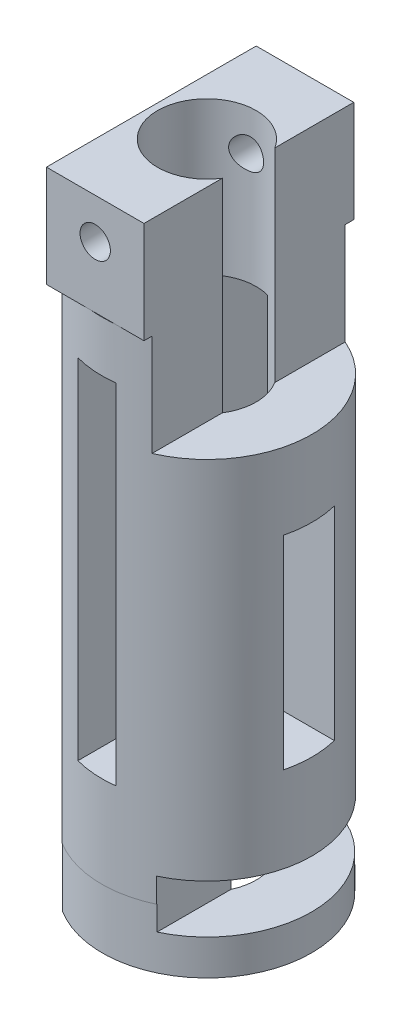
SolidWorks part; units mm, degrees
ref_plane "前基準面" through (0, 0, 0) normal (0, 0, 1) x (1, 0, 0)
ref_plane "上基準面" through (0, 0, 0) normal (0, 1, 0) x (1, 0, 0)
ref_plane "右基準面" through (0, 0, 0) normal (1, 0, 0) x (0, 0, -1)
sketch "草圖1" plane through (0, 0, 0) normal (0, 1, 0) x (1, 0, 0)
  circle A0 centre (0, 0) radius 9.7
  dimension "D1" = 19.4
extrude "伸長-薄件1" add sketch "草圖1" along normal blind 116.68 thin
ref_plane "平面1" through (-21, 0, 0) normal (1, 0, 0) x (0, 0, -1)
sketch "草圖11" plane through (0, 116.68, 0) normal (0, 1, 0) x (1, 0, 0)
  line L0 (-993.1634, -44.2358) -> (49006.8366, -44.2358) construction
  line L2 (35.2085, 30.7642) -> (8.2085, 30.7642)
  line L3 (35.2085, 30.7642) -> (35.2085, -119.2358)
  line L4 (35.2085, -119.2358) -> (8.2085, -119.2358)
  line L5 (8.2085, 30.7642) -> (8.2085, -119.2358)
  line L6 (35.2085, 30.7642) -> (8.2085, -119.2358) construction
  line L7 (35.2085, -119.2358) -> (8.2085, 30.7642) construction
  circle A0 centre (0, 0) radius 20.7 construction
  point P1 (21.7085, -44.2358)
  dimension "D1" = 150
  dimension "D2" = 27
  dimension "D3" = 30.7642
extrude "除料-伸長3" cut sketch "草圖11" against normal blind 40
ref_plane "平面2" through (0, 0, 21) normal (0, 0, 1) x (1, 0, 0)
sketch "草圖13" plane through (0, 0, 21) normal (0, 0, 1) x (1, 0, 0)
  line L0 (-21, -22.649) -> (-21, 22.649) construction
  line L1 (-21, 122.7847) -> (-11, 122.7847)
  line L2 (-21, 122.7847) -> (-21, -5.5603)
  line L3 (-21, -5.5603) -> (-11, -5.5603)
  line L4 (-11, 122.7847) -> (-11, -5.5603)
  dimension "D1" = 10
extrude "除料-伸長7" cut sketch "草圖13" against normal through all
sketch "草圖15" plane through (0, 0, 21) normal (0, 0, 1) x (1, 0, 0)
  line L0 (-1.3957, -883.32) -> (-1.3957, 49116.68) construction
  line L1 (8.2085, 116.68) -> (-11, 116.68) construction
  line L2 (-11, 0) -> (20.7, 0) construction
  line L3 (2.6043, 86.68) -> (-5.3957, 86.68)
  line L4 (2.6043, 86.68) -> (2.6043, 18)
  line L5 (2.6043, 18) -> (-5.3957, 18)
  line L6 (-5.3957, 86.68) -> (-5.3957, 18)
  line L7 (2.6043, 86.68) -> (-5.3957, 18) construction
  line L8 (2.6043, 18) -> (-5.3957, 86.68) construction
  point P1 (-1.3957, 52.34)
  point P5 (-1.3957, 116.68)
  dimension "D1" = 30
  dimension "D2" = 18
  dimension "D3" = 8
extrude "除料-伸長9" cut sketch "草圖15" against normal blind 48
sketch "草圖16" plane through (8.2085, 0, 0) normal (1, 0, 0) x (0, 0, -1)
  line L0 (20.7, 86.68) -> (20.7, 116.68) construction
  line L1 (5.1682, 116.68) -> (20.7, 116.68)
  line L2 (5.1682, 116.68) -> (5.1682, 96.68)
  line L3 (5.1682, 96.68) -> (20.7, 96.68)
  line L4 (20.7, 116.68) -> (20.7, 96.68)
  line L5 (-5.1682, 76.68) -> (-5.1682, 116.68) construction
  line L6 (-5.1682, 96.68) -> (-20.59, 96.68)
  line L7 (-5.1682, 96.68) -> (-5.1682, 116.68)
  line L8 (-5.1682, 116.68) -> (-20.59, 116.68)
  line L9 (-20.59, 96.68) -> (-20.59, 116.68)
  line L10 (-17.5354, 116.68) -> (-20.7, 116.68) construction
  dimension "D1" = 20
extrude "填料-伸長4" add sketch "草圖16" against normal blind 19.2
sketch "草圖17" plane through (0, 116.68, 0) normal (0, 1, 0) x (1, 0, 0)
  line L0 (-1009.59, 0) -> (48990.41, 0) construction
  line L1 (8.2085, 20.7) -> (8.2085, 5.1682) construction
  line L2 (8.2085, 6.97) -> (-11, 6.97)
  line L3 (8.2085, 6.97) -> (8.2085, -7.06)
  line L4 (8.2085, -7.06) -> (-11, -7.06)
  line L5 (-11, 6.97) -> (-11, -7.06)
  line L6 (-11, -17.5354) -> (-11, 17.5354) construction
  line L7 (-10.9915, -20.59) -> (-2.1312, -20.59) construction
  arc A0 (-8.2085, 5.1682) -> (-8.2085, -5.1682) centre (0, 0) ccw construction
  point P6 (-9.7, 0)
  dimension "D1" = 14.03
  dimension "D2" = 13.53
sketch "草圖21" plane through (0, 0, -20.7) normal (0, 0, -1) x (-1, 0, 0)
  line L0 (1.3915, 96.68) -> (1.3915, 105.73) construction
  line L1 (0, 96.68) -> (10.9915, 96.68) construction
  line L2 (1.3915, 105.73) -> (1.3915, 108.73) construction
  circle A0 centre (1.3915, 108.73) radius 2.985
  dimension "D3" = 5.97
  dimension "D1" = 9.05
  dimension "D2" = 3
extrude "除料-伸長12" cut sketch "草圖21" against normal blind 55.2
sketch "草圖23" plane through (0, 0, -20.7) normal (0, 0, -1) x (-1, 0, 0)
  line L0 (1.3915, 105.745) -> (1.3915, -11.785) construction
  circle A0 centre (1.3915, 108.73) radius 2.985 construction
  dimension "D1" = 117.53
sketch "草圖24" plane through (0, 0, 0) normal (0, -1, 0) x (1, 0, 0)
  circle A0 centre (0, 0) radius 9.59
extrude "伸長-薄件2" add sketch "草圖24" along normal blind 55.2 thin
sketch "草圖25" plane through (0, 0, 21) normal (0, 0, 1) x (1, 0, 0)
  line L0 (-1.3915, -11.785) -> (22.6124, -11.785)
  line L1 (22.6124, -11.785) -> (22.6124, -63.8733)
  line L2 (-22.7495, -63.8733) -> (22.6124, -63.8733)
  line L3 (-22.7495, -63.8733) -> (-22.7495, -11.785)
  line L4 (-22.7495, -11.785) -> (-1.3915, -11.785)
extrude "除料-伸長13" cut sketch "草圖25" against normal blind 55.2
sketch "草圖26" plane through (0, 0, 0) normal (0, 1, 0) x (1, 0, 0)
  line L0 (-21, -22.649) -> (-21, 22.649) construction
  line L1 (-10.9915, 20.7) -> (-21, 20.7)
  line L2 (-10.9915, 20.7) -> (-10.9915, -21)
  line L3 (-10.9915, -21) -> (-21, -21)
  line L4 (-21, 20.7) -> (-21, -21)
  line L5 (-25.6693, -21) -> (25.6693, -21) construction
extrude "除料-伸長15" cut sketch "草圖26" against normal blind 55.2
ref_plane "平面3" through (21, 0, 0) normal (1, 0, 0) x (0, 0, -1)
sketch "草圖27" plane through (21, 0, 0) normal (1, 0, 0) x (0, 0, -1)
  line L0 (0, -923.32) -> (0, 49076.68) construction
  line L1 (5.1682, 76.68) -> (-5.1682, 76.68) construction
  line L2 (19.0029, 76.68) -> (-19.0029, 76.68) construction
  line L3 (-5, 61.68) -> (5, 61.68)
  line L4 (-5, 61.68) -> (-5, 21.68)
  line L5 (-5, 21.68) -> (5, 21.68)
  line L6 (5, 61.68) -> (5, 21.68)
  line L7 (-5, 61.68) -> (5, 21.68) construction
  line L8 (-5, 21.68) -> (5, 61.68) construction
  point P1 (0, 41.68)
  point P5 (0, 76.68)
  dimension "D1" = 15
  dimension "D2" = 40
  dimension "D3" = 10
extrude "除料-伸長16" cut sketch "草圖27" against normal blind 55.2
sketch "草圖28" plane through (21, 0, 0) normal (1, 0, 0) x (0, 0, -1)
  line L1 (-22.4403, 4.804) -> (22.4403, 4.804)
  line L2 (-22.4403, 4.804) -> (-22.4403, -4.804)
  line L3 (-22.4403, -4.804) -> (22.4403, -4.804)
  line L4 (22.4403, 4.804) -> (22.4403, -4.804)
  line L5 (-22.4403, 4.804) -> (22.4403, -4.804) construction
  line L6 (-22.4403, -4.804) -> (22.4403, 4.804) construction
  point P0 (0, 0)
extrude "除料-伸長17" cut sketch "草圖28" against normal blind 12.2
ref_plane "平面4" through (0, 0, 50) normal (0, 0, 1) x (1, 0, 0)
sketch "草圖63" plane through (0, -11.785, 0) normal (0, -1, 0) x (1, 0, 0)
  circle A0 centre (0, 0) radius 9.59
extrude "除料-伸長36" cut sketch "草圖63" against normal blind 130
sketch "草圖64" plane through (0, -11.785, 0) normal (0, -1, 0) x (1, 0, 0)
  circle A0 centre (0, 0) radius 9.7
  dimension "D1" = 19.4
extrude "除料-伸長37" cut sketch "草圖64" against normal through all
sketch "草圖66" plane through (0, 116.68, 0) normal (0, 1, 0) x (1, 0, 0)
  line L1 (2.1312, -20.59) -> (-2.1879, -20.59)
  line L2 (2.1312, -20.59) -> (2.1312, -21.3905)
  line L3 (2.1312, -21.3905) -> (-2.1879, -21.3905)
  line L4 (-2.1879, -20.59) -> (-2.1879, -21.3905)
extrude "除料-伸長39" cut sketch "草圖66" against normal blind 20
